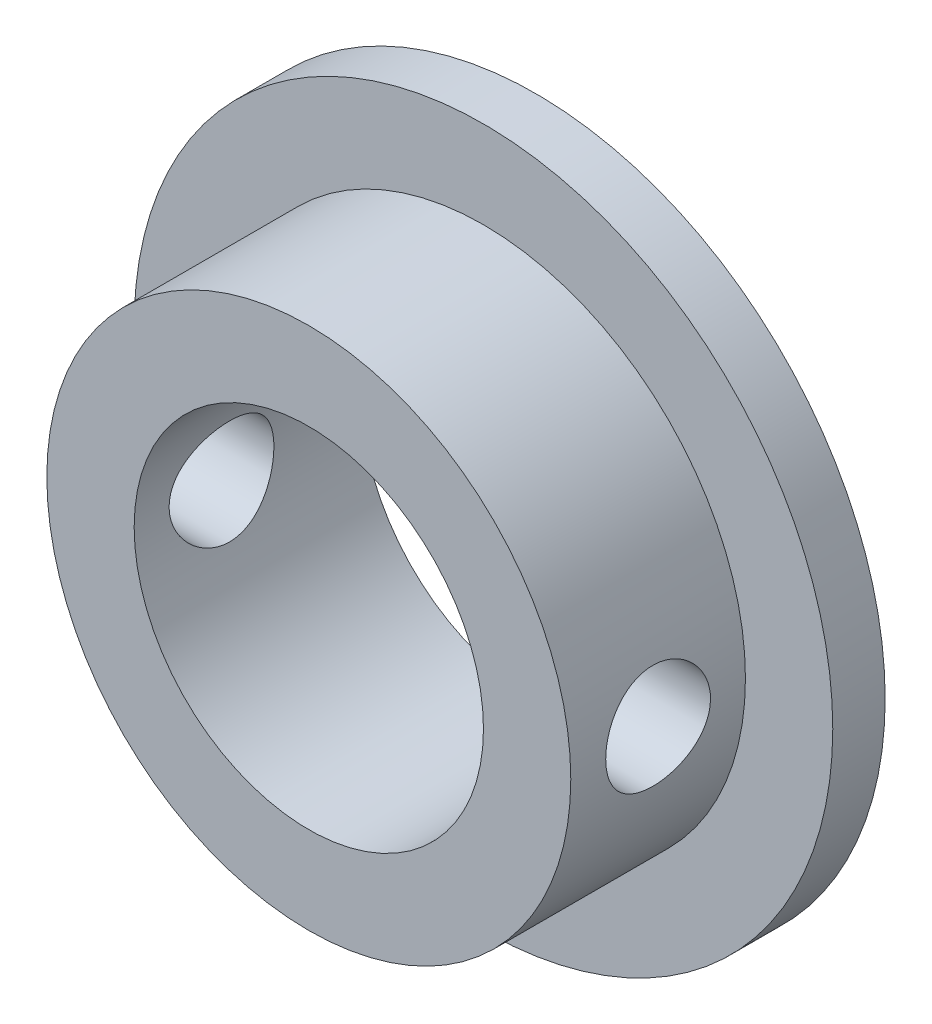
SolidWorks part; units mm, degrees
ref_plane "前视基准面" through (0, 0, 0) normal (0, 0, 1) x (1, 0, 0)
ref_plane "上视基准面" through (0, 0, 0) normal (0, 1, 0) x (1, 0, 0)
ref_plane "右视基准面" through (0, 0, 0) normal (1, 0, 0) x (0, 0, -1)
sketch "草图1" plane through (0, 0, 0) normal (0, 0, 1) x (1, 0, 0)
  circle A0 centre (0, 0) radius 10
  dimension "D1" = 20
extrude "凸台-拉伸1" add sketch "草图1" along normal blind 1.5 contours A0
sketch "草图2" plane through (0, 0, 1.5) normal (0, 0, 1) x (1, 0, 0)
  circle A0 centre (0, 0) radius 7.5
  dimension "D1" = 15
extrude "凸台-拉伸2" add sketch "草图2" along normal blind 5
sketch "草图3" plane through (0, 0, 6.5) normal (0, 0, 1) x (1, 0, 0)
  circle A0 centre (0, 0) radius 5
  dimension "D1" = 10
extrude "切除-拉伸1" cut sketch "草图3" against normal through all
ref_plane "基准面4" through (7.5, 0, 0) normal (1, 0, 0) x (0, 0, -1)
sketch "草图4" plane through (7.5, 0, 0) normal (1, 0, 0) x (0, 0, -1)
  line L0 (-6.5, 0) -> (-1.5, 0) construction
  line L1 (-6.5, 7.5) -> (-6.5, -7.5) construction
  line L2 (-1.5, 7.5) -> (-1.5, -7.5) construction
  line L3 (-1.5, 0) -> (3.8152, -2.2476) construction
  circle A0 centre (-4, 0) radius 1.5
  dimension "D1" = 3
extrude "切除-拉伸2" cut sketch "草图4" against normal through all
